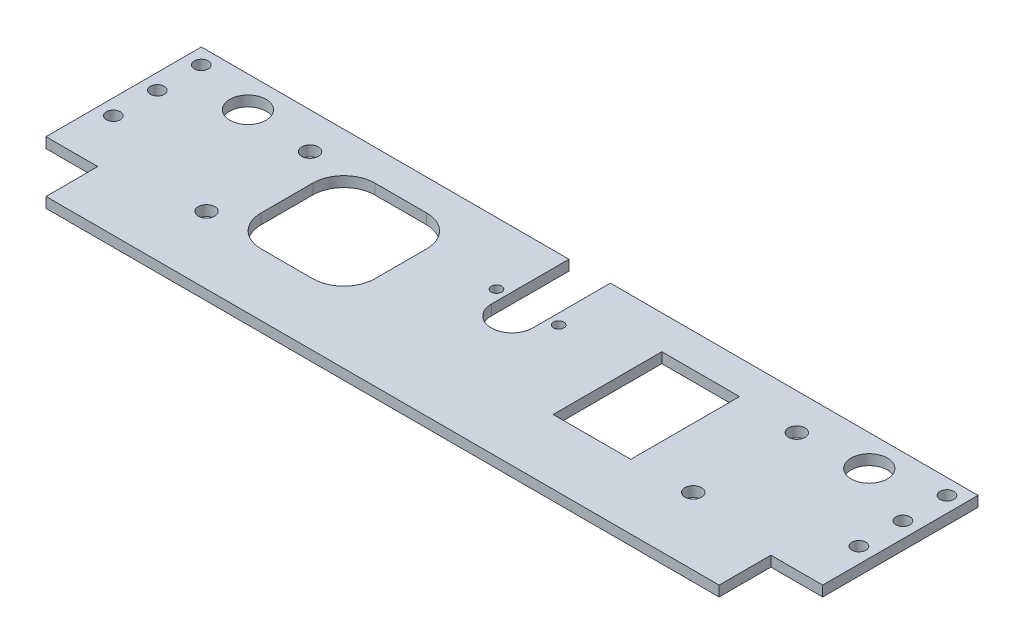
SolidWorks part; units mm, degrees
ref_plane "前视基准面" through (0, 0, 0) normal (0, 0, 1) x (1, 0, 0)
ref_plane "上视基准面" through (0, 0, 0) normal (0, 1, 0) x (1, 0, 0)
ref_plane "右视基准面" through (0, 0, 0) normal (1, 0, 0) x (0, 0, -1)
sketch "草图1" plane through (0, 0, 0) normal (0, 1, 0) x (1, 0, 0)
  line L0 (-58.8971, 0) -> (44.3681, 0) construction
  line L1 (-75, 17) -> (-4, 17)
  line L2 (-75, 17) -> (-75, -17)
  line L3 (-75, -17) -> (-2.5, -17) construction
  line L4 (75, 17) -> (75, -17)
  line L5 (-75, 17) -> (75, -17) construction
  line L6 (-75, -17) -> (75, 17) construction
  line L7 (0, -15) -> (0, 17) construction
  line L33 (-4, 17) -> (-4, 2)
  line L34 (-4, 2) -> (4, 2) construction
  line L36 (2.5, -17) -> (75, -17) construction
  line L38 (-41.48, 11) -> (-19.48, 11)
  line L39 (-41.48, 11) -> (-41.48, -11)
  line L40 (-41.48, -11) -> (-19.48, -11)
  line L41 (-19.48, 11) -> (-19.48, -11)
  line L42 (-41.48, 11) -> (-19.48, -11) construction
  line L43 (-41.48, -11) -> (-19.48, 11) construction
  line L44 (20.44, 10.5) -> (35.44, 10.5)
  line L45 (20.44, 10.5) -> (20.44, -10.5)
  line L46 (20.44, -10.5) -> (35.44, -10.5)
  line L47 (35.44, 10.5) -> (35.44, -10.5)
  line L48 (20.44, 10.5) -> (35.44, -10.5) construction
  line L49 (20.44, -10.5) -> (35.44, 10.5) construction
  line L54 (-75, -17) -> (-75, -23)
  line L55 (-75, -23) -> (75, -23)
  line L56 (75, -23) -> (75, -17)
  line L57 (4, 2) -> (4, 17)
  line L58 (4, 17) -> (75, 17)
  circle A0 centre (-72, 14) radius 1.35
  circle A8 centre (-72, -3) radius 1.35
  circle A9 centre (72, -3) radius 1.35
  circle A10 centre (72, 14) radius 1.35
  circle A18 centre (-60, 11) radius 3.5
  circle A19 centre (60, 11) radius 3.5
  circle A20 centre (-47, 10) radius 1.6
  circle A23 centre (47, 10) radius 1.6
  circle A24 centre (47, -10) radius 1.6
  circle A25 centre (-47, -10) radius 1.6
  arc A26 (-4, 2) -> (4, 2) centre (0, 2) ccw
  circle A27 centre (-6, 5) radius 1
  circle A28 centre (6, 5) radius 1
  circle A29 centre (-72, 5.5) radius 1.35
  circle A30 centre (72, 5.5) radius 1.35
  point P0 (0, 0)
  point P18 (0, 0)
  point P41 (-30.48, 0)
  point P49 (27.94, 0)
  dimension "D3" = 2.7
  dimension "D6" = 4
  dimension "D25" = 6
  dimension "D9" = 6
  dimension "D11" = 7
  dimension "D15" = 3.2
  dimension "D18" = 22
  dimension "D16" = 22
  dimension "D23" = 12
  dimension "D10" = 2
  dimension "D1" = 150
  dimension "D2" = 34
  dimension "D4" = 72
  dimension "D5" = 3
  dimension "D7" = 4
  dimension "D8" = 15
  dimension "D12" = 15
  dimension "D13" = 6
  dimension "D14" = 10
  dimension "D17" = 47
  dimension "D19" = 30.48
  dimension "D20" = 27.94
  dimension "D21" = 15
  dimension "D22" = 21
  dimension "D24" = 17
  dimension "D26" = 8.5
extrude "凸台-拉伸1" add sketch "草图1" along normal blind 2
fillet "圆角1" radius 6 4 edges at (-19.48, 1, -11) (-19.48, 1, 11) (-41.48, 1, 11) (-41.48, 1, -11)
sketch "草图2" plane through (0, 0, 0) normal (0, -1, 0) x (1, 0, 0)
  line L0 (0, 0) -> (0, 48.4322) construction
  line L1 (-75, -17) -> (-75, 23) construction
  line L2 (-81.044, 38.9172) -> (-65, 38.9172)
  line L3 (-81.044, 38.9172) -> (-81.044, 13)
  line L4 (-81.044, 13) -> (-65, 13)
  line L5 (-65, 38.9172) -> (-65, 13)
  line L6 (-75, 23) -> (75, 23) construction
  line L7 (81.044, 13) -> (65, 13)
  line L8 (65, 38.9172) -> (65, 13)
  line L9 (81.044, 38.9172) -> (81.044, 13)
  line L10 (81.044, 38.9172) -> (65, 38.9172)
  dimension "D1" = 10
  dimension "D2" = 10
extrude "切除-拉伸1" cut sketch "草图2" against normal through all
